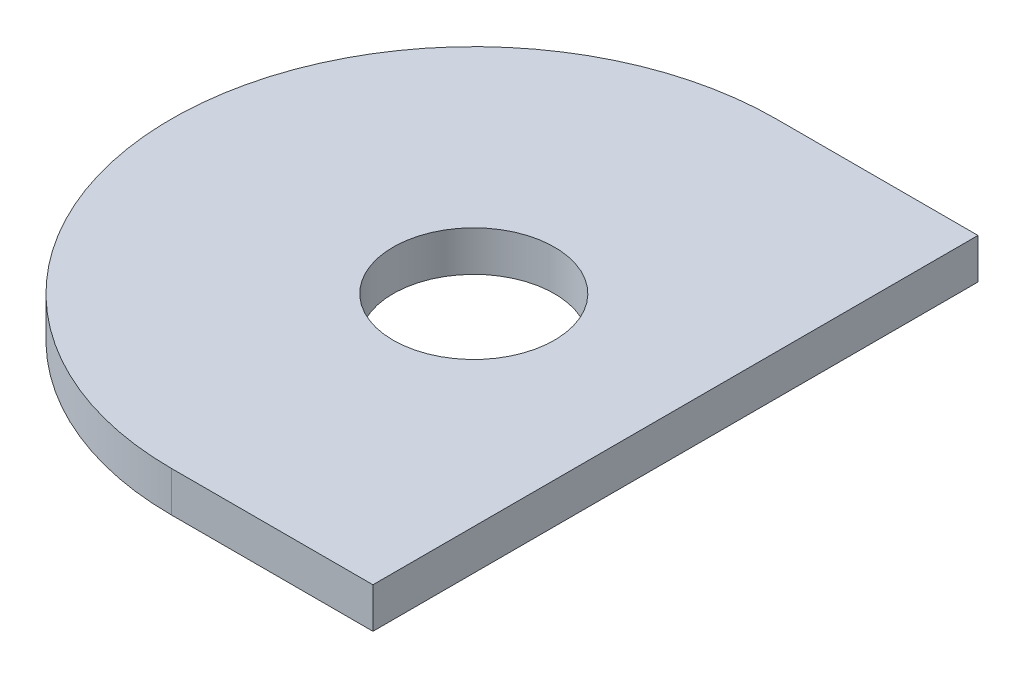
SolidWorks part; units mm, degrees
ref_plane "Front Plane" through (0, 0, 0) normal (0, 0, 1) x (1, 0, 0)
ref_plane "Top Plane" through (0, 0, 0) normal (0, 1, 0) x (1, 0, 0)
ref_plane "Right Plane" through (0, 0, 0) normal (1, 0, 0) x (0, 0, -1)
sketch "Sketch1" plane through (0, 0, 0) normal (0, 1, 0) x (1, 0, 0)
  line L0 (0, 0) -> (0, 60) construction
  line L1 (0, 60) -> (20, 60)
  line L2 (20, 60) -> (20, 0)
  line L3 (20, 0) -> (0, 0)
  arc A0 (0, 60) -> (0, 0) centre (0, 30) ccw
  circle A1 centre (0, 30) radius 8
  dimension "D1" = 60
  dimension "D3" = 16
  dimension "D2" = 20
extrude "Boss-Extrude1" add sketch "Sketch1" along normal blind 4
